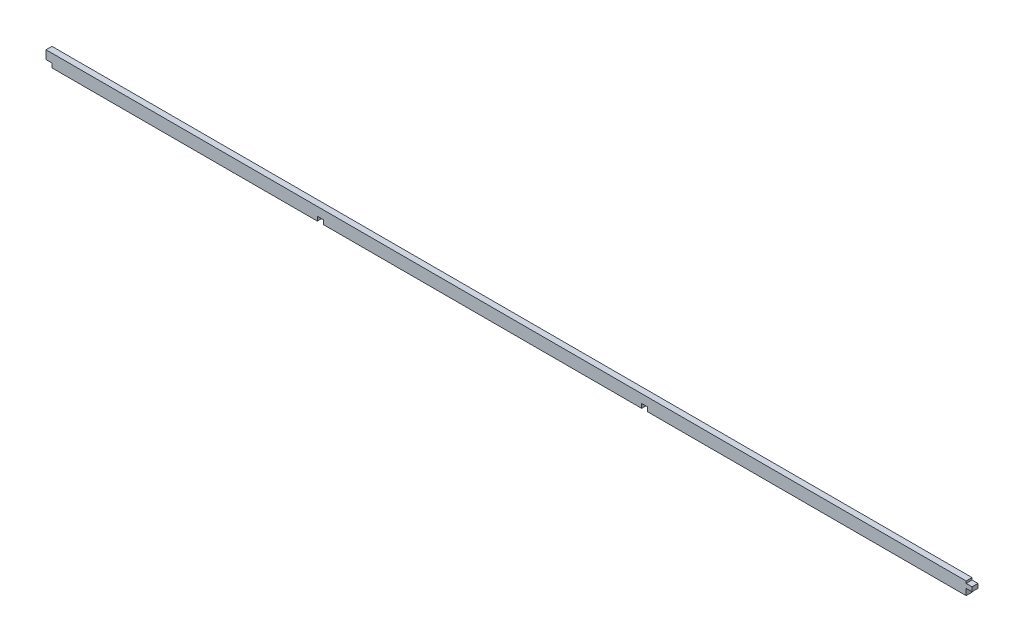
SolidWorks part; units mm, degrees
material "Фанера"
ref_plane "Front Plane" through (0, 0, 0) normal (0, 0, 1) x (1, 0, 0)
ref_plane "Top Plane" through (0, 0, 0) normal (0, 1, 0) x (1, 0, 0)
ref_plane "Right Plane" through (0, 0, 0) normal (1, 0, 0) x (0, 0, -1)
sketch "Эскиз1" plane through (0, 0, 0) normal (0, 0, 1) x (1, 0, 0)
  line L0 (0, -4) -> (2.8, -4)
  line L1 (2.8, -6) -> (127.8, -6)
  line L2 (0, -4) -> (0, 0)
  line L3 (0, 0) -> (433.4, 0)
  line L4 (127.8, 20.0008) -> (127.8, -17.954) construction
  line L5 (130.6, 18.2809) -> (130.6, -12.6588) construction
  line L6 (2.8, -4) -> (2.8, -6)
  line L7 (280.6, 21.1399) -> (280.6, -20.4716) construction
  line L8 (283.4, 21.1399) -> (283.4, -16.4614) construction
  line L9 (127.8, -6) -> (127.8, -4)
  line L10 (127.8, -4) -> (130.6, -4)
  line L11 (130.6, -4) -> (130.6, -6)
  line L12 (130.6, -6) -> (280.6, -6)
  line L13 (280.6, -6) -> (280.6, -4)
  line L14 (280.6, -4) -> (283.4, -4)
  line L15 (283.4, -4) -> (283.4, -6)
  line L16 (283.4, -6) -> (433.4, -6)
  line L17 (433.4, 0) -> (433.4, -1)
  line L18 (420.6815, -4) -> (449.0477, -4) construction
  line L19 (433.4, -3) -> (433.4, -6)
  line L20 (433.4, -3) -> (436.2, -3)
  line L22 (433.4, -1) -> (436.2, -1)
  line L23 (436.2, -3) -> (436.2, -1)
  line L24 (433.4, -2) -> (436.2, -1) construction
  line L25 (433.4, -2) -> (436.2, -3) construction
  point P0 (420.6815, -3)
  point P25 (0, 0)
  point P26 (433.4, -2)
  point P28 (211.3106, 4.8703)
  point P29 (0, 0)
  dimension "D1" = 4
  dimension "D2" = 433.4
  dimension "D3" = 2.8
  dimension "D4" = 125
  dimension "D5" = 2.8
  dimension "D6" = 4
  dimension "D7" = 150
  dimension "D8" = 2.8
  dimension "D9" = 4
  dimension "D10" = 4
  dimension "D11" = 2
  dimension "D12" = 2
  dimension "D13" = 1
  dimension "D14" = 2.8
  dimension "D15" = 6
extrude "Бобышка-Вытянуть1" add sketch "Эскиз1" along normal mid plane 2.8
